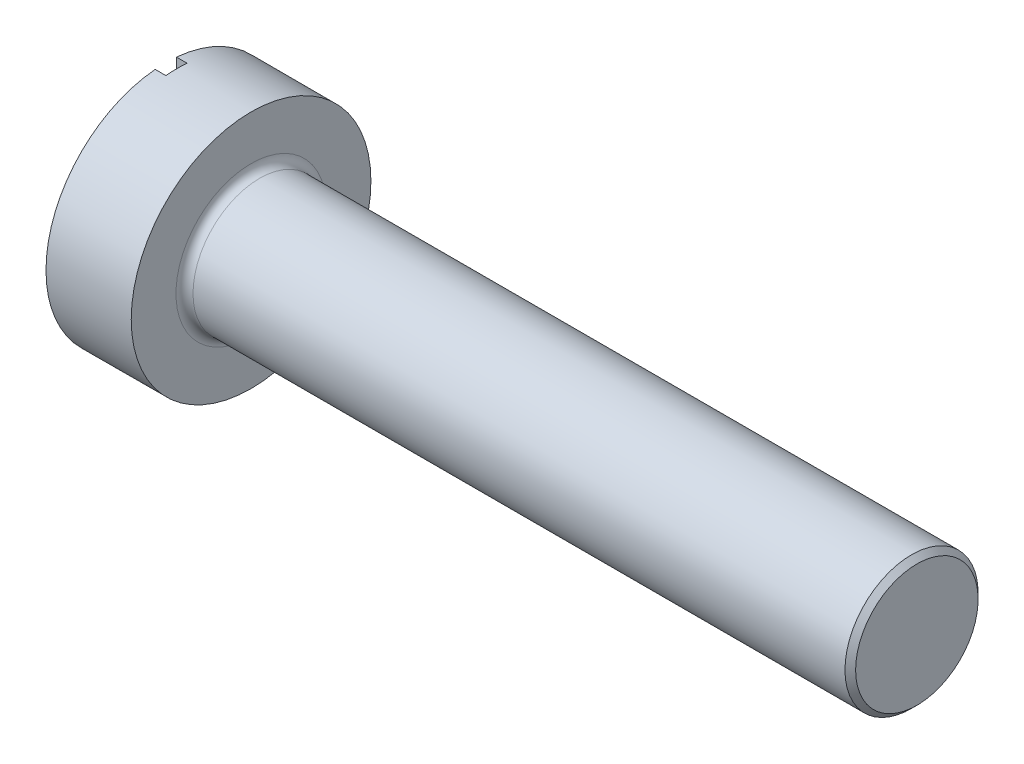
SolidWorks part; units mm, degrees
ref_plane "Front Plane" through (0, 0, 0) normal (0, 0, 1) x (1, 0, 0)
ref_plane "Top Plane" through (0, 0, 0) normal (0, 1, 0) x (1, 0, 0)
ref_plane "Right Plane" through (0, 0, 0) normal (1, 0, 0) x (0, 0, -1)
sketch "Sketch1" plane through (0, 0, 0) normal (0, 0, 1) x (1, 0, 0)
  line L0 (0, 0) -> (0, 2.25)
  line L1 (0, 2.25) -> (1.6, 2.25)
  line L2 (1.6, 2.25) -> (1.6, 0.75)
  line L3 (0, 0) -> (14.1, 0)
  line L4 (14.1, 0) -> (14.1, 1.25)
  line L5 (14.1, 1.25) -> (1.6, 1.25)
  dimension "D1" = 2.25
  dimension "D2" = 1.6
  dimension "D3" = 12.5
  dimension "D4" = 1.25
revolve "Revolve1" add sketch "Sketch1" angle 360 about L3
chamfer "Chamfer1" distance 0.1 angle 45 1 edges at (14.1, 0, 1.25)
fillet "Fillet1" radius 0.16 1 edges at (1.6, 0, 1.25)
sketch "Sketch2" plane through (0, 0, 0) normal (0, 1, 0) x (1, 0, 0)
  line L1 (0, 0) -> (0.2, 0)
  line L2 (0, 0) -> (0, 0.2)
  line L3 (0, 0.2) -> (0.2, 0.2)
  line L4 (0.2, 0) -> (0.2, 0.2)
  line L5 (0, 0) -> (0.2, 0)
  line L6 (0, 0) -> (0, -0.2)
  line L7 (0, -0.2) -> (0.2, -0.2)
  line L8 (0.2, 0) -> (0.2, -0.2)
extrude "Extrude1" cut sketch "Sketch2" against normal through all both and the other way through all contours L8 L1 L6 L7 | L1 L4 L3 L2
